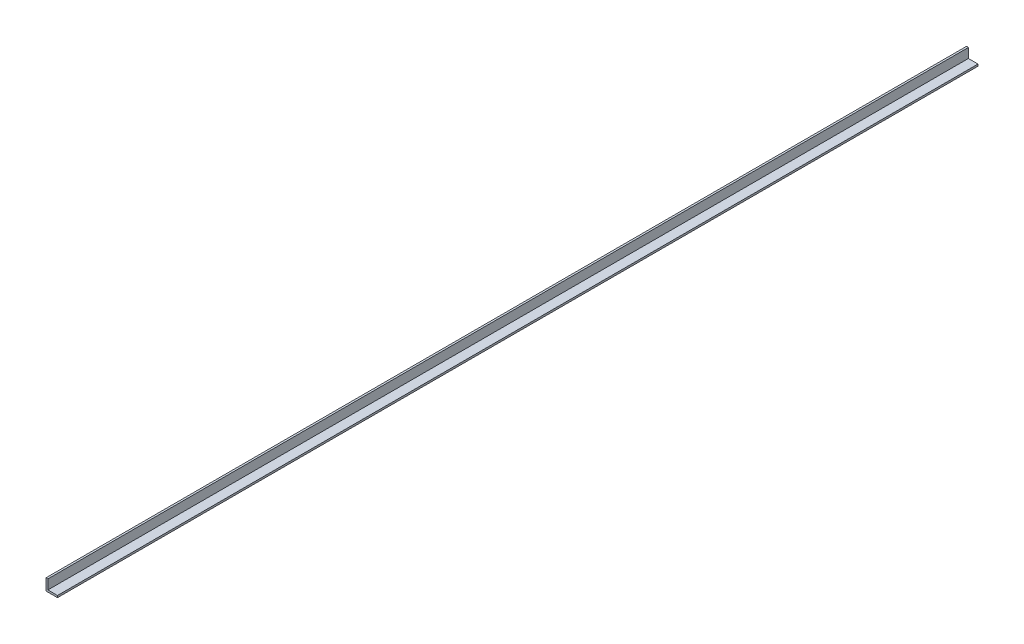
SolidWorks part; units mm, degrees
material "ASTM A36 Acero"
ref_plane "Alzado" through (0, 0, 0) normal (0, 0, 1) x (1, 0, 0)
ref_plane "Planta" through (0, 0, 0) normal (0, 1, 0) x (1, 0, 0)
ref_plane "Vista lateral" through (0, 0, 0) normal (1, 0, 0) x (0, 0, -1)
sketch "Croquis1" plane through (0, 0, 0) normal (0, 0, 1) x (1, 0, 0)
  line L0 (0, 76.2) -> (0, 0)
  line L1 (0, 0) -> (76.2, 0)
  line L2 (76.2, 0) -> (76.2, 12.7)
  line L3 (76.2, 12.7) -> (12.7, 12.7)
  line L4 (12.7, 12.7) -> (12.7, 76.2)
  line L5 (12.7, 76.2) -> (0, 76.2)
  dimension "D1" = 12.7
  dimension "D2" = 76.2
extrude "Saliente-Extruir1" add sketch "Croquis1" against normal blind 6100
